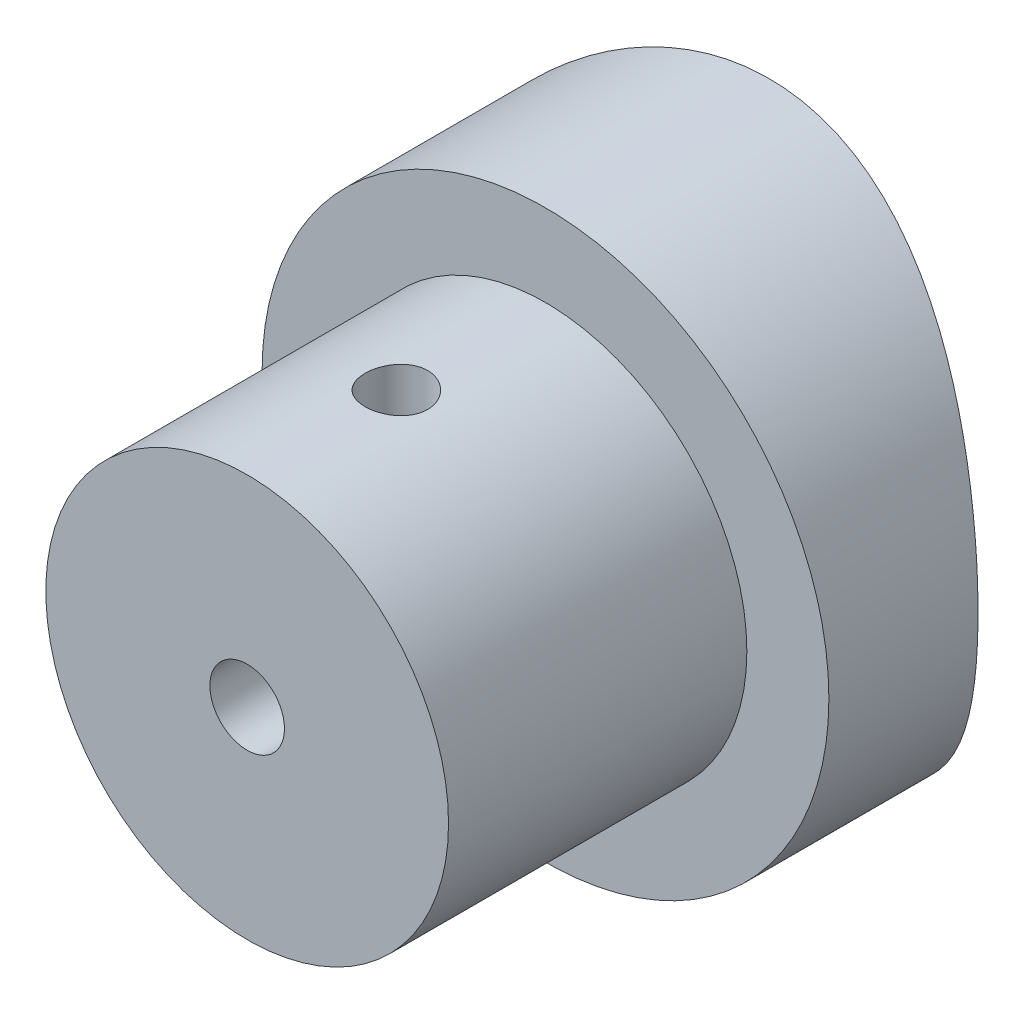
SolidWorks part; units mm, degrees
material "Alumina"
ref_plane "Plano frontal" through (0, 0, 0) normal (0, 0, 1) x (1, 0, 0)
ref_plane "Plano superior" through (0, 0, 0) normal (0, 1, 0) x (1, 0, 0)
ref_plane "Plano direito" through (0, 0, 0) normal (1, 0, 0) x (0, 0, -1)
sketch "Esboço1" plane through (0, 0, 0) normal (0, 0, 1) x (1, 0, 0)
  circle A0 centre (0, 0) radius 19
  dimension "D1" = 38
extrude "Ressalto-extrusão1" add sketch "Esboço1" along normal mid plane 15
sketch "Esboço2" plane through (0, 0, 0) normal (0, 1, 0) x (1, 0, 0)
  line L0 (-19, 7.5) -> (-19, -7.5) construction
  line L1 (19, -7.5) -> (19, 7.5) construction
  line L2 (19, 7.5) -> (-19, 7.5) construction
  arc A0 (-19, 2.5) -> (19, 2.5) centre (0, -31.1) cw
  dimension "D1" = 5
  dimension "D2" = 5
extrude "Corte-extrusão1" cut sketch "Esboço2" against normal through all and the other way through all
sketch "Esboço3" plane through (0, 0, 7.5) normal (0, 0, 1) x (1, 0, 0)
  circle A0 centre (0, 0) radius 13.5
  dimension "D1" = 27
extrude "Ressalto-extrusão2" add sketch "Esboço3" along normal blind 20
hole_wizard "Furo roscado de M61" positions "Esboço4" profile "Esboço5" tap size "M6" standard "DIN" end condition through all
sketch "Esboço4" plane through (0, 0, 27.5) normal (0, 0, 1) x (1, 0, 0)
  point P0 (0, 0)
sketch "Esboço5" plane through (0, 0, 27.5) normal (1, 0, 0) x (0, -1, 0)
  line L0 (0, 0) -> (0, 35)
  line L1 (0, 35) -> (2.5, 35)
  line L2 (2.5, 35) -> (2.5, 0)
  line L5 (2.5, 0) -> (0, 0)
  line L11 (0, -6.35) -> (0, 107.95) construction
  dimension "Thru Tap Drill Dia." = 5
  dimension "Thru Tap Drill Depth" = 35
cosmetic thread "Rosca de furo1" parameters "D2"=6
ref_plane "Plano1" through (0, 14, 0) normal (0, 1, 0) x (1, 0, 0)
hole_wizard "Furo roscado de M51" positions "Esboço8" profile "Esboço9" tap size "M5" standard "DIN"
sketch "Esboço8" plane through (0, 14, 0) normal (0, 1, 0) x (1, 0, 0)
  line L0 (-13.5, -7.5) -> (13.5, -7.5) construction
  point P0 (0, -17.5)
  dimension "D1" = 10
sketch "Esboço9" plane through (0, 14, 17.5) normal (1, 0, 0) x (0, 0, 1)
  line L0 (0, 0) -> (0, 11.2618)
  line L1 (0, 11.2618) -> (2.1, 10)
  line L2 (2.1, 10) -> (2.1, 0)
  line L5 (2.1, 0) -> (0, 0)
  line L10 (0, 11.2618) -> (-2.1, 10) construction
  line L11 (0, -6.35) -> (0, 107.95) construction
  dimension "Tap Drill Dia." = 4.2
  dimension "Tap Drill Depth" = 10
  dimension "Drill Angle" = 118
cosmetic thread "Rosca de furo2" parameters "D1"=10, "D2"=5
